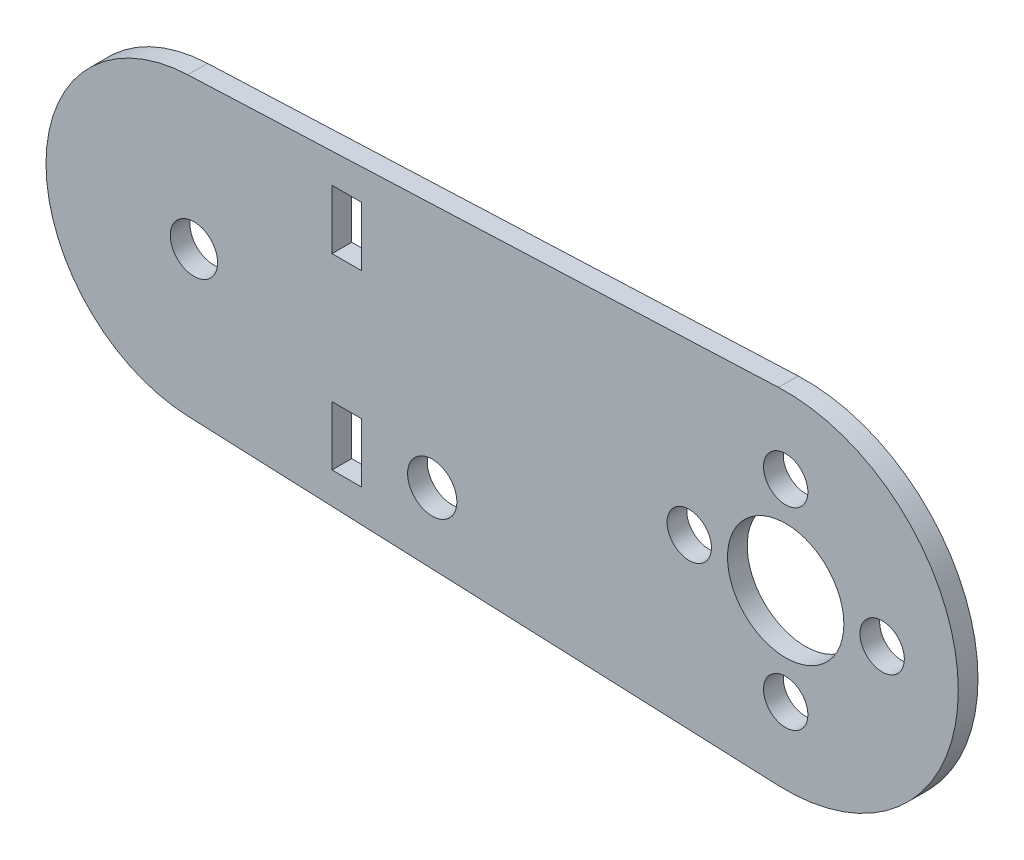
SolidWorks part; units mm, degrees
ref_plane "Front Plane" through (0, 0, 0) normal (0, 0, 1) x (1, 0, 0)
ref_plane "Top Plane" through (0, 0, 0) normal (0, 1, 0) x (1, 0, 0)
ref_plane "Right Plane" through (0, 0, 0) normal (1, 0, 0) x (0, 0, -1)
sketch "Sketch1" plane through (0, 0, 0) normal (0, 0, 1) x (1, 0, 0)
  line L0 (-60.625, 14.987) -> (-0.7292, 17.4848)
  line L1 (-60.625, -14.987) -> (-0.7292, -17.4848)
  circle A0 centre (0, 0) radius 5.9
  circle A1 centre (0, 0) radius 17.5
  circle A2 centre (-60, 0) radius 15
  dimension "D1" = 11.8
  dimension "D2" = 35
  dimension "D3" = 30
  dimension "D4" = 60
extrude "Boss-Extrude1" add sketch "Sketch1" along normal blind 2 contours A1 A0 | A2 | A2 L1 A1 L0
sketch "Sketch2" plane through (0, 0, 2) normal (0, 0, 1) x (1, 0, 0)
  circle A0 centre (0, 9.78) radius 2.25
  circle A1 centre (0, 0) radius 5.9 construction
  circle A2 centre (9.78, 0) radius 2.25
  circle A3 centre (0, -9.78) radius 2.25
  circle A4 centre (-9.78, 0) radius 2.25
  point P10 (0, 0)
  dimension "D1" = 4.5
  dimension "D2" = 9.78
  dimension "D3" = 4
extrude "Cut-Extrude1" cut sketch "Sketch2" against normal through all
sketch "Sketch3" plane through (0, 0, 2) normal (0, 0, 1) x (1, 0, 0)
  circle A0 centre (-60, 0) radius 2.4
  arc A1 (-60.625, 14.987) -> (-60.625, -14.987) centre (-60, 0) ccw construction
  dimension "D1" = 4.8
extrude "Cut-Extrude2" cut sketch "Sketch3" against normal through all
sketch "Sketch4" plane through (0, 0, 2) normal (0, 0, 1) x (1, 0, 0)
  line L1 (-46, 12.5943) -> (-43, 12.5943)
  line L2 (-46, 12.5943) -> (-46, -12.4057)
  line L3 (-46, -12.4057) -> (-43, -12.4057)
  line L4 (-43, 12.5943) -> (-43, -12.4057)
  line L5 (-60.625, 14.987) -> (-0.7292, 17.4848) construction
  line L8 (-46, -12.4057) -> (-43, -12.4057)
  line L9 (-46, -12.4057) -> (-46, -6.4057)
  line L10 (-46, -6.4057) -> (-43, -6.4057)
  line L11 (-43, -12.4057) -> (-43, -6.4057)
  line L12 (-46, 12.5943) -> (-43, 12.5943)
  line L13 (-46, 12.5943) -> (-46, 6.5943)
  line L14 (-46, 6.5943) -> (-43, 6.5943)
  line L15 (-43, 12.5943) -> (-43, 6.5943)
  circle A0 centre (-60, 0) radius 12.5
  dimension "D1" = 25
  dimension "D2" = 3
  dimension "D3" = 14
  dimension "D4" = 25
  dimension "D5" = 3
  dimension "D6" = 6
  dimension "D7" = 6
extrude "Cut-Extrude3" cut sketch "Sketch4" against normal blind 10 contours L10 L2 L3 L4 | L2 L14 L4 L1
sketch "Sketch5" plane through (0, 0, 2) normal (0, 0, 1) x (1, 0, 0)
  circle A0 centre (-35.8403, -8.8752) radius 2.5
  circle A1 centre (-35.8403, -8.8752) radius 5
  dimension "D1" = 5
  dimension "D3" = 10
extrude "Cut-Extrude4" cut sketch "Sketch5" against normal through all contours A0
